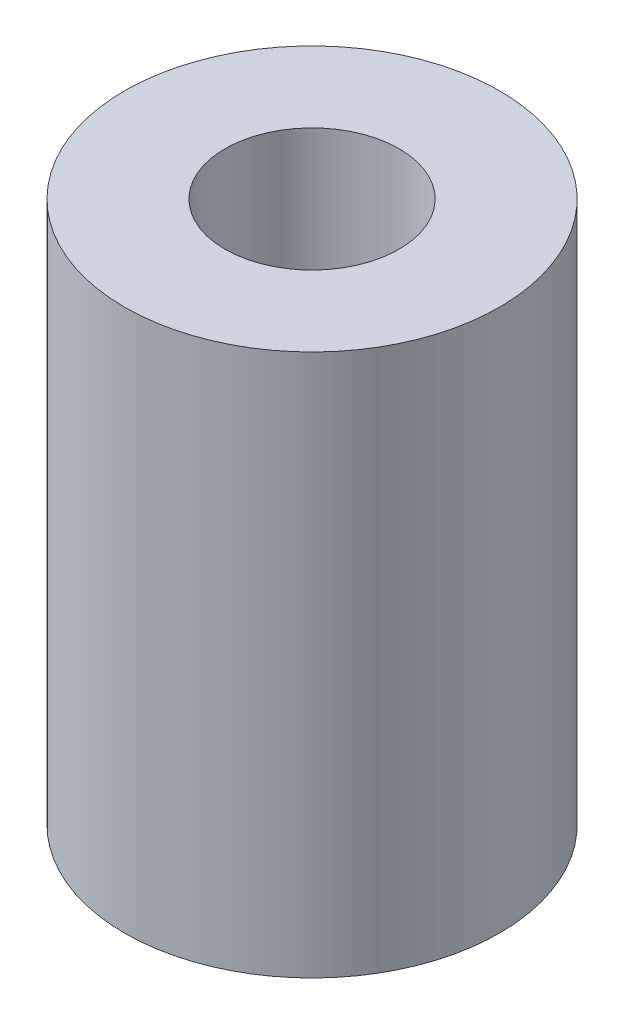
SolidWorks part; units mm, degrees
ref_plane "Front Plane" through (0, 0, 0) normal (0, 0, 1) x (1, 0, 0)
ref_plane "Top Plane" through (0, 0, 0) normal (0, 1, 0) x (1, 0, 0)
ref_plane "Right Plane" through (0, 0, 0) normal (1, 0, 0) x (0, 0, -1)
sketch "Sketch1" plane through (0, 0, 0) normal (0, 1, 0) x (1, 0, 0)
  circle A0 centre (0, 0) radius 4.1275
  circle A1 centre (0, 0) radius 1.9177
  dimension "D1" = 8.255
  dimension "D2" = 3.8354
extrude "Boss-Extrude1" add sketch "Sketch1" along normal blind 11.938
